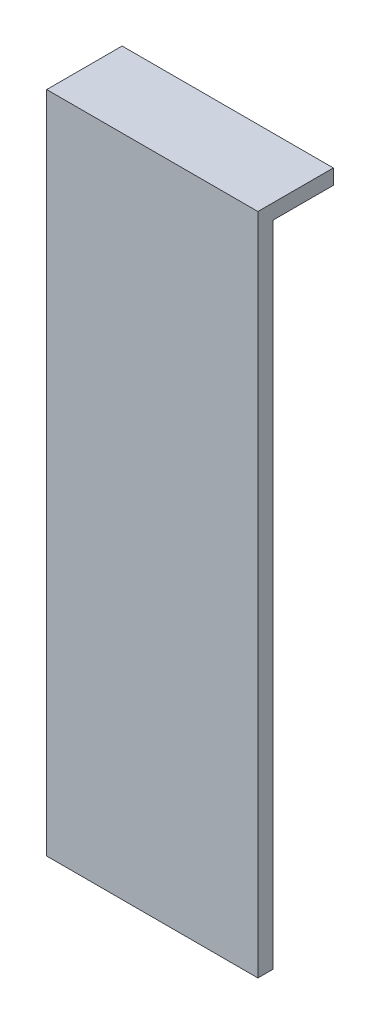
SolidWorks part; units mm, degrees
ref_plane "Front Plane" through (0, 0, 0) normal (0, 0, 1) x (1, 0, 0)
ref_plane "Top Plane" through (0, 0, 0) normal (0, 1, 0) x (1, 0, 0)
ref_plane "Right Plane" through (0, 0, 0) normal (1, 0, 0) x (0, 0, -1)
sketch "Sketch3" plane through (0, 0, 0) normal (0, 0, 1) x (1, 0, 0)
  line L0 (35.75, 0) -> (-35.75, 0) construction
  line L1 (-102.4311, 110) -> (-32.4311, 110)
  line L2 (-102.4311, 110) -> (-102.4311, -110)
  line L3 (-102.4311, -110) -> (-32.4311, -110)
  line L4 (-32.4311, 110) -> (-32.4311, -110)
  line L5 (-102.4311, 110) -> (-32.4311, -110) construction
  line L6 (-102.4311, -110) -> (-32.4311, 110) construction
  point P0 (-67.4311, 0)
  dimension "D1" = 70
  dimension "D2" = 220
extrude "Boss-Extrude2" add sketch "Sketch3" along normal blind 5
sketch "Sketch4" plane through (0, 0, 0) normal (0, 0, 1) x (1, 0, 0)
  line L1 (-102.4311, -110) -> (-97.4311, -110)
  line L2 (-102.4311, -110) -> (-102.4311, -10)
  line L3 (-102.4311, -10) -> (-97.4311, -10)
  line L4 (-97.4311, -110) -> (-97.4311, -10)
  dimension "D1" = 100
  dimension "D2" = 5
extrude "Boss-Extrude3" add sketch "Sketch4" against normal blind 10
sketch "Sketch5" plane through (0, 0, 0) normal (0, 0, 1) x (1, 0, 0)
  line L0 (-102.4311, 110) -> (-102.4311, -10) construction
  line L1 (-32.4311, 110) -> (-102.4311, 110)
  line L2 (-32.4311, 110) -> (-32.4311, 105)
  line L3 (-32.4311, 105) -> (-102.4311, 105)
  line L4 (-102.4311, 110) -> (-102.4311, 105)
  dimension "D1" = 5
extrude "Boss-Extrude4" add sketch "Sketch5" against normal blind 20
